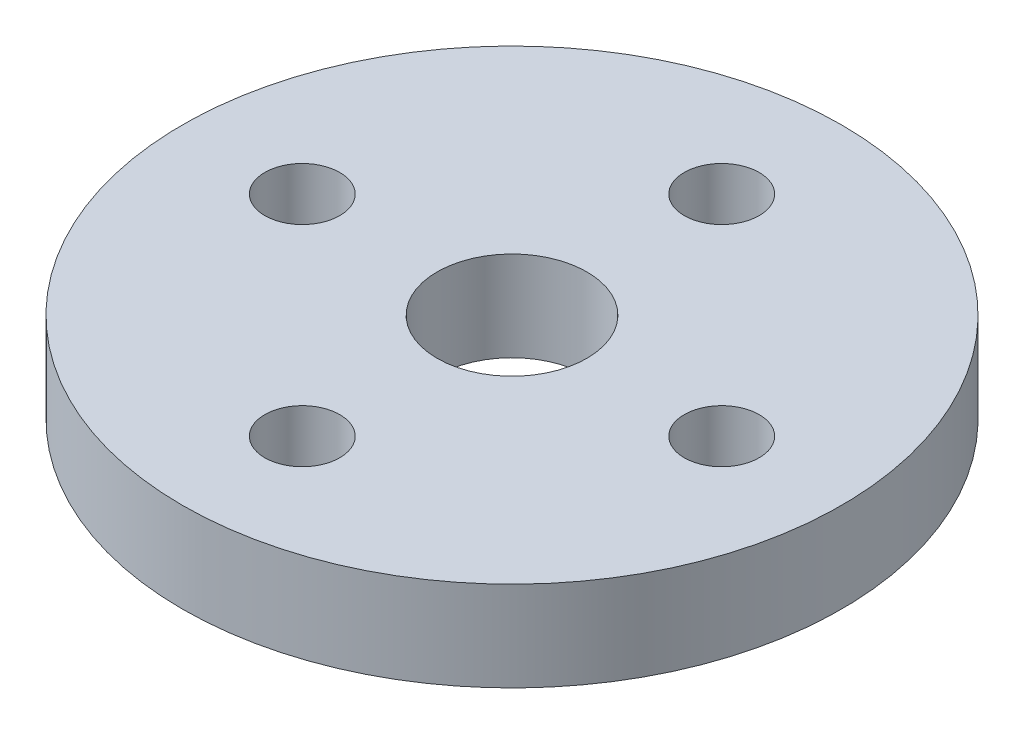
SolidWorks part; units mm, degrees
ref_plane "Front Plane" through (0, 0, 0) normal (0, 0, 1) x (1, 0, 0)
ref_plane "Top Plane" through (0, 0, 0) normal (0, 1, 0) x (1, 0, 0)
ref_plane "Right Plane" through (0, 0, 0) normal (1, 0, 0) x (0, 0, -1)
sketch "Sketch1" plane through (0, 0, 0) normal (0, 1, 0) x (1, 0, 0)
  circle A0 centre (0, 0) radius 11
  circle A1 centre (0, 0) radius 2.5
  circle A2 centre (0, 0) radius 7 construction
  circle A3 centre (0, 7) radius 1.25
  circle A4 centre (7, 0) radius 1.25
  circle A5 centre (0, -7) radius 1.25
  circle A6 centre (-7, 0) radius 1.25
  dimension "D1" = 5
  dimension "D2" = 14
  dimension "D3" = 22
  dimension "D4" = 2.5
extrude "Boss-Extrude1" add sketch "Sketch1" along normal blind 3
